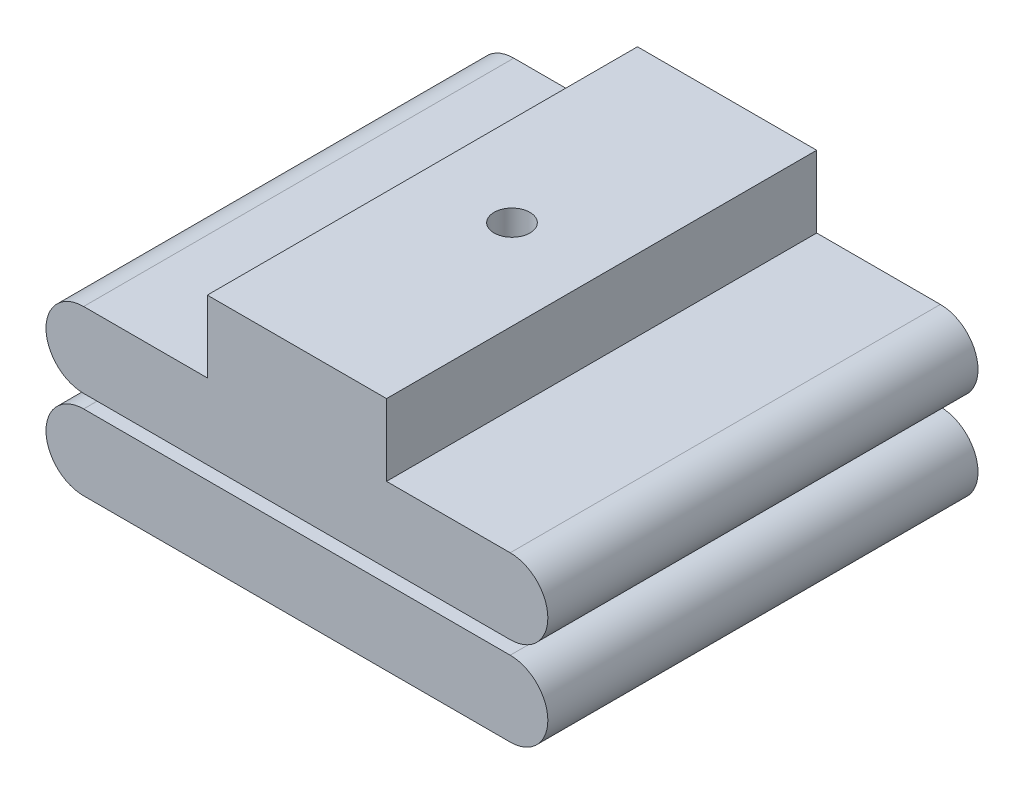
SolidWorks part; units mm, degrees
other "Markup1"
sketch "Sketch11" plane through (14, 8, 12.5) normal (0.5259, 0.0132, 0.8504) x (0.8493, 0.0463, -0.5259)
sketch "Sketch12" plane through (14, 4, 12) normal (0.5259, 0.0132, 0.8504) x (0.8493, 0.0463, -0.5259)
material "Silicon Rubber"
ref_plane "Front Plane" through (0, 0, 0) normal (0, 0, 1) x (1, 0, 0)
ref_plane "Top Plane" through (0, 0, 0) normal (0, 1, 0) x (1, 0, 0)
ref_plane "Right Plane" through (0, 0, 0) normal (1, 0, 0) x (0, 0, -1)
sketch "Sketch1" plane through (0, 0, 0) normal (0, 0, 1) x (1, 0, 0)
  line L0 (-14, -2.1) -> (-14, 49997.9) construction
  line L1 (-11.9, 0) -> (11.9, 0)
  line L2 (-11.9, -1.6) -> (11.9, -1.6)
  line L3 (-11.9, -2.6) -> (11.9, -2.6)
  line L4 (-11.9, -4.2) -> (11.9, -4.2)
  line L5 (14, -2.1) -> (14, 49997.9) construction
  arc A0 (-11.9, 0) -> (-11.9, -4.2) centre (-11.9, -2.1) ccw
  arc A1 (-11.9, -1.6) -> (-11.9, -2.6) centre (-11.9, -2.1) ccw
  arc A2 (11.9, -1.6) -> (11.9, -2.6) centre (11.9, -2.1) cw
  arc A3 (11.9, 0) -> (11.9, -4.2) centre (11.9, -2.1) cw
  point P2 (-14, -2.1)
  point P6 (0, 0)
  point P9 (0, -1.6)
  point P14 (0, -2.6)
  point P15 (0, -4.2)
  point P19 (14, -2.1)
  dimension "D1" = 28
  dimension "D2" = 1.6
  dimension "D3" = 1
extrude "Boss-Extrude1" add sketch "Sketch1" along normal blind 10
sketch "Sketch3" plane through (0, 0, 10) normal (0, 0, 1) x (1, 0, 0)
  line L0 (-11.9, -4.2) -> (11.9, -4.2) construction
  line L1 (0, 0) -> (0, -4.2) construction
  line L3 (-11.9, -1.6) -> (11.9, -1.6)
  line L7 (-12.4, -2.1) -> (12.4, -2.1)
  arc A0 (-12.4, -2.1) -> (-11.9, -1.6) centre (-11.9, -2.1) cw
  arc A1 (-11.9, -1.6) -> (-11.9, -2.6) centre (-11.9, -2.1) ccw construction
  arc A5 (12.4, -2.1) -> (11.9, -1.6) centre (11.9, -2.1) ccw
sketch "Sketch4" plane through (0, 0, 10) normal (0, 0, 1) x (1, 0, 0)
  line L7 (11.9, 0) -> (-11.9, 0)
  line L8 (-11.9, -4.2) -> (11.9, -4.2)
  line L9 (11.9, 0) -> (-11.9, 0)
  line L10 (-11.9, -4.2) -> (11.9, -4.2)
  arc A3 (11.9, -4.2) -> (11.9, 0) centre (11.9, -2.1) ccw
  arc A4 (-11.9, 0) -> (-11.9, -4.2) centre (-11.9, -2.1) ccw
  arc A5 (11.9, -4.2) -> (11.9, 0) centre (11.9, -2.1) ccw
  arc A6 (-11.9, 0) -> (-11.9, -4.2) centre (-11.9, -2.1) ccw
  dimension "D1" = 0
extrude "Boss-Extrude2" add sketch "Sketch4" along normal blind 2
revolve "Cut-Revolve1" cut sketch "Sketch3" angle 180 about L7
mirror "Mirror1" about plane through (0, 0, 0) normal (0, 0, 1) of "Boss-Extrude1", "Cut-Revolve1", "Boss-Extrude2"
sketch "Sketch5" plane through (0, 0, 0) normal (0, 0, 1) x (1, 0, 0)
  line L0 (0, 0) -> (0, -22) construction
  dimension "D1" = 22
pattern_linear "LPattern1" count 2 spacing 4.95 along (0, -1, 0) of bodies 108
sketch "Sketch6" plane through (0, 0, 0) normal (0, 0, 1) x (1, 0, 0)
  line L1 (-11.9, -4.2) -> (11.9, -4.2) construction
  line L2 (11.9, -4.95) -> (-11.9, -4.95) construction
  line L6 (0, 0) -> (0, -50000) construction
  line L7 (-3.775, -4.2) -> (-1, -4.2)
  line L8 (-1, -4.2) -> (-1, -4.95)
  line L9 (-1, -4.95) -> (-3.775, -4.95)
  line L10 (-3.4, -4.95) -> (-3.4, -4.2) construction
  arc A0 (-3.775, -4.2) -> (-3.775, -4.95) centre (-3.775, -4.575) cw
  point P15 (-3.4, -4.575)
  dimension "D1" = 2.4
  dimension "D2" = 1
revolve "Revolve1" add sketch "Sketch6" angle 360 about L6
sketch "Sketch7" plane through (0, 0, 0) normal (0, 1, 0) x (1, 0, 0)
  circle A0 centre (0, 0) radius 1
  circle A1 centre (0, 0) radius 1 construction
extrude "Cut-Extrude1" cut sketch "Sketch7" against normal up to surface (7.55 mm away) up to face at (0, -7.55, 0)
sketch "Sketch8" plane through (0, 0, 0) normal (0, 1, 0) x (1, 0, 0)
  line L0 (11.9, 12) -> (-11.9, 12) construction
  line L1 (-5, 12) -> (5, 12)
  line L2 (-5, 12) -> (-5, -12)
  line L3 (-5, -12) -> (5, -12)
  line L4 (5, 12) -> (5, -12)
  circle A0 centre (0, 0) radius 1 construction
  circle A1 centre (0, 0) radius 1
  point P6 (0, 12)
  point P8 (-5, 0)
  dimension "D1" = 10
extrude "Boss-Extrude3" add sketch "Sketch8" along normal blind 4
fillet "Fillet1" radius 1 3 edges at (0, -6.55, -1) (0, -2.6, 1) (0, -1.6, -1)
sketch "Sketch10" plane through (0, 0, 0) normal (1, 0, 0) x (0, 0, -1)
  line L1 (0.5, 2.3) -> (0.5, 1.5)
  line L2 (1, 2.3) -> (1, 4)
  line L4 (0, 0) -> (0, 2.0258) construction
  line L6 (0.5, 2.3) -> (1, 2.3) construction
  line L8 (1, 4) -> (0.5, 2.3)
  line L9 (0.5, 1.5) -> (1, 1.5)
  line L10 (1, 1.5) -> (1, 2.3)
  dimension "D1" = 0.5
  dimension "D2" = 2.5
  dimension "D3" = 0.8
revolve "Revolve2" [suppressed] add sketch "Sketch10" angle 360 about L4
